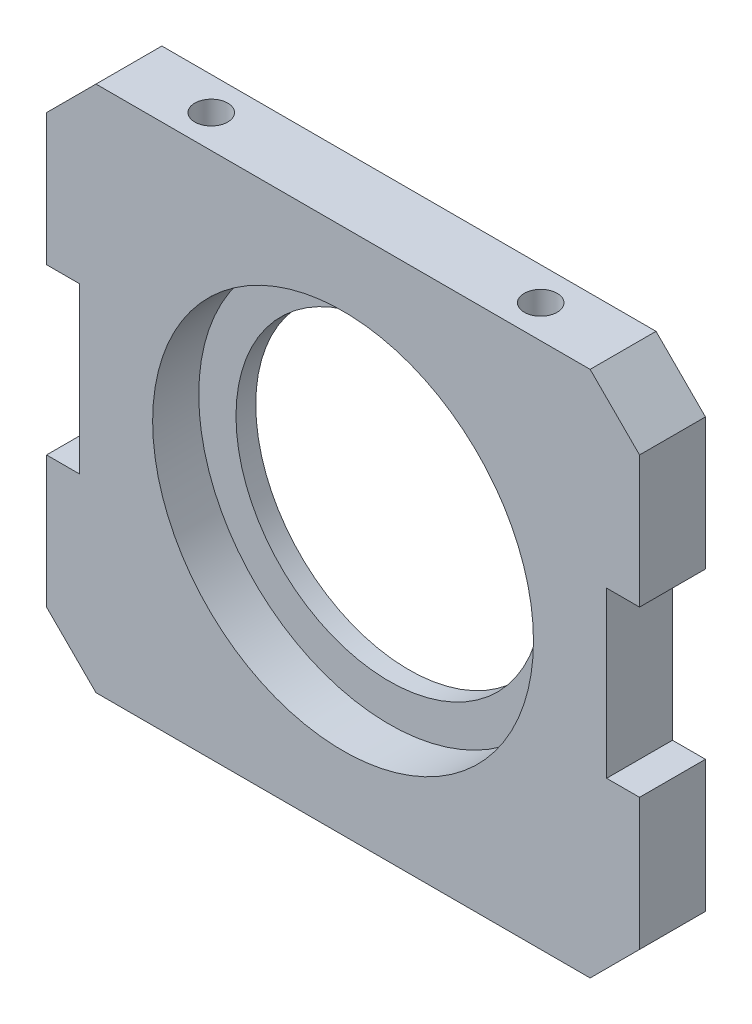
SolidWorks part; units mm, degrees
material "ABS"
ref_plane "Alzado" through (0, 0, 0) normal (0, 0, 1) x (1, 0, 0)
ref_plane "Planta" through (0, 0, 0) normal (0, 1, 0) x (1, 0, 0)
ref_plane "Vista lateral" through (0, 0, 0) normal (1, 0, 0) x (0, 0, -1)
sketch "Croquis1" plane through (0, 0, 0) normal (0, 0, 1) x (1, 0, 0)
  line L1 (-45, -40) -> (45, -40)
  line L2 (-45, -40) -> (-45, 40)
  line L3 (-45, 40) -> (45, 40)
  line L4 (45, -40) -> (45, 40)
  line L5 (-45, -40) -> (45, 40) construction
  line L6 (-45, 40) -> (45, -40) construction
  line L7 (-35, -20) -> (35, -20) construction
  line L8 (-35, -20) -> (-35, 20) construction
  line L9 (-35, 20) -> (35, 20) construction
  line L10 (35, -20) -> (35, 20) construction
  line L11 (-35, -20) -> (35, 20) construction
  line L12 (-35, 20) -> (35, -20) construction
  circle A0 centre (0, 0) radius 28.9
  circle A1 centre (35, 20) radius 2.25 construction
  circle A2 centre (35, -20) radius 2.25 construction
  circle A3 centre (-35, -20) radius 2.25 construction
  circle A4 centre (-35, 20) radius 2.25 construction
  point P0 (0, 0)
  dimension "D1" = 57.8
  dimension "D5" = 4.5
  dimension "D2" = 90
  dimension "D3" = 70
  dimension "D4" = 40
  dimension "D6" = 80
extrude "Saliente-Extruir1" add sketch "Croquis1" along normal mid plane 10
sketch "Croquis2" plane through (0, 0, -5) normal (0, 0, -1) x (-1, 0, 0)
  circle A0 centre (0, 0) radius 28.9 construction
  circle A1 centre (0, 0) radius 28.9
  circle A2 centre (0, 0) radius 23.25
  dimension "D1" = 46.5
extrude "Saliente-Extruir2" add sketch "Croquis2" against normal blind 3
sketch "Croquis4" plane through (0, 0, 5) normal (0, 0, 1) x (1, 0, 0)
  line L0 (-45, 40) -> (-45, -40) construction
  line L1 (-50, -12.5) -> (-40, -12.5)
  line L2 (-50, -12.5) -> (-50, 12.5)
  line L3 (-50, 12.5) -> (-40, 12.5)
  line L4 (-40, -12.5) -> (-40, 12.5)
  line L5 (-50, -12.5) -> (-40, 12.5) construction
  line L6 (-50, 12.5) -> (-40, -12.5) construction
  line L7 (0, -5.5) -> (0, 5.5) construction
  line L8 (50, 12.5) -> (40, 12.5)
  line L9 (40, -12.5) -> (40, 12.5)
  line L10 (50, -12.5) -> (40, -12.5)
  line L11 (50, -12.5) -> (50, 12.5)
  point P0 (-45, 0)
  dimension "D1" = 25
  dimension "D2" = 10
extrude "Cortar-Extruir2" cut sketch "Croquis4" against normal through all
chamfer "Chaflán2" distance 7.5 angle 45 4 edges at (-45, -40, 0) (45, -40, 0) (45, 40, 0) (-45, 40, 0)
sketch "Croquis9" plane through (0, -40, 0) normal (0, -1, 0) x (1, 0, 0)
  line L0 (25, 0) -> (-25, 0) construction
  circle A0 centre (-25, 0) radius 2.5
  circle A1 centre (25, 0) radius 2.5
  point P4 (0, 0)
  dimension "D2" = 5
  dimension "D1" = 50
extrude "Cortar-Extruir3" cut sketch "Croquis9" against normal blind 10
mirror "Simetría1" about plane through (0, 0, 0) normal (0, 1, 0) of "Cortar-Extruir3"
